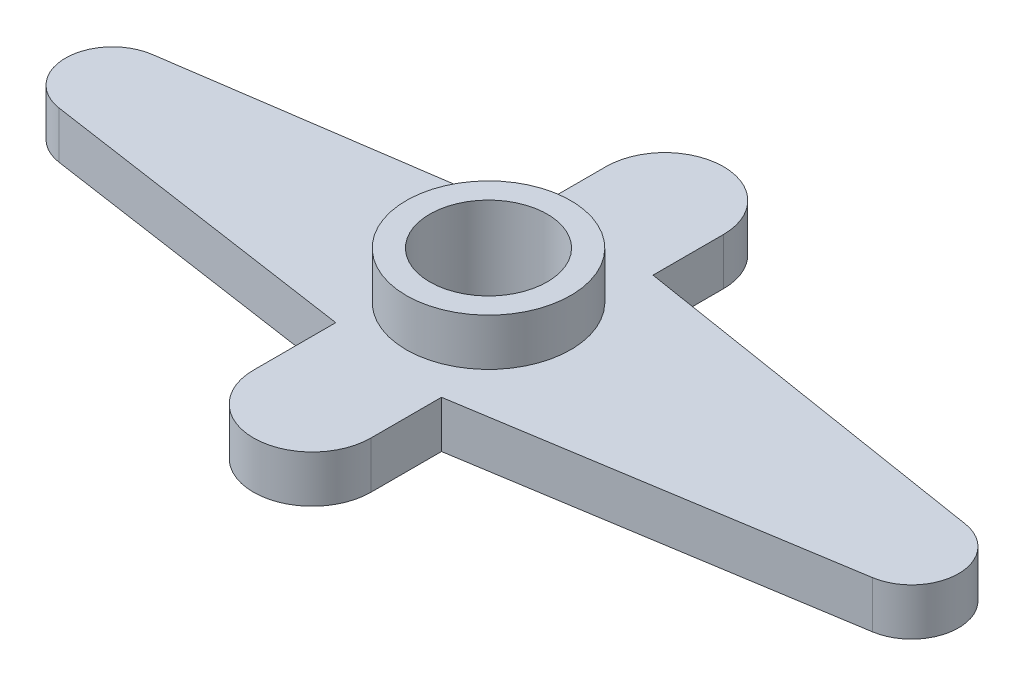
SolidWorks part; units mm, degrees
ref_plane "Front Plane" through (0, 0, 0) normal (0, 0, 1) x (1, 0, 0)
ref_plane "Top Plane" through (0, 0, 0) normal (0, 1, 0) x (1, 0, 0)
ref_plane "Right Plane" through (0, 0, 0) normal (1, 0, 0) x (0, 0, -1)
sketch "Sketch1" plane through (0, 0, 0) normal (0, 1, 0) x (1, 0, 0)
  circle A0 centre (0, 0) radius 3.5
  circle A1 centre (0, 0) radius 2.5
  dimension "D1" = 7
  dimension "D2" = 1
extrude "Boss-Extrude1" add sketch "Sketch1" along normal blind 4
sketch "Sketch2" plane through (0, 0, 0) normal (0, 1, 0) x (1, 0, 0)
  line L0 (0, 0) -> (20, 0) construction
  line L1 (0, 0) -> (-18, 0) construction
  line L2 (0, -10) -> (0, 10) construction
  line L3 (-2.5, 2.4495) -> (-2.5, 7.5)
  line L4 (2.5, 4.5) -> (2.5, 0)
  line L5 (2.5, 7.5) -> (2.5, 2.4495)
  line L6 (-2.5, -2.4495) -> (-2.5, -7.5)
  line L7 (2.5, -7.5) -> (2.5, -2.4495)
  line L8 (2.5, 4.5) -> (18.3153, 1.975)
  line L9 (2.5, -4.5) -> (18.3153, -1.975)
  line L10 (2.5, 0) -> (2.5, -4.5)
  line L15 (-2.5, -4) -> (-2.5, 0)
  line L16 (-2.5, -4) -> (-16.29, -1.9789)
  line L17 (-2.5, 4) -> (-16.29, 1.9789)
  line L18 (-2.5, 0) -> (-2.5, 4)
  arc A0 (-2.5, 2.4495) -> (2.5, 2.4495) centre (0, 0) cw
  arc A1 (-2.5, 7.5) -> (2.5, 7.5) centre (0, 7.5) cw
  arc A2 (-2.5, -7.5) -> (2.5, -7.5) centre (0, -7.5) ccw
  circle A3 centre (0, 0) radius 3.5 construction
  arc A4 (-2.5, -2.4495) -> (2.5, -2.4495) centre (0, 0) ccw
  arc A5 (18.3153, 1.975) -> (18.3153, -1.975) centre (18, 0) cw
  circle A7 centre (0, 0) radius 2.5 construction
  arc A10 (-16.29, 1.9789) -> (-16.29, -1.9789) centre (-16, 0) ccw
  arc A11 (-1.106, 2.2421) -> (-2.5, 0) centre (0, 0) ccw
  point P7 (0, 0)
  point P13 (0, 10)
  point P24 (20, 0)
  point P41 (-18, 0)
  dimension "D6" = 2
  dimension "D8" = 2
  dimension "D1" = 20
  dimension "D2" = 18
  dimension "D3" = 20
  dimension "D4" = 5
  dimension "D5" = 9
  dimension "D7" = 8
extrude "Boss-Extrude2" add sketch "Sketch2" along normal blind 2
